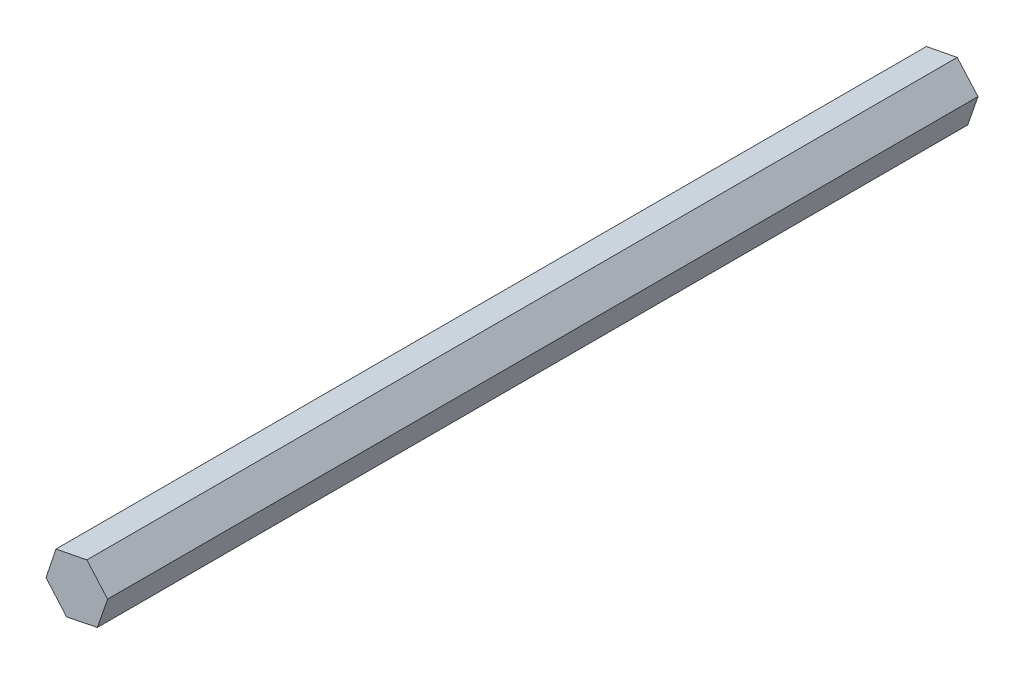
SolidWorks part; units mm, degrees
material "6061 Alloy"
ref_plane "Front Plane" through (0, 0, 0) normal (0, 0, 1) x (1, 0, 0)
ref_plane "Top Plane" through (0, 0, 0) normal (0, 1, 0) x (1, 0, 0)
ref_plane "Right Plane" through (0, 0, 0) normal (1, 0, 0) x (0, 0, -1)
ref_plane "Plane1" through (0, 0, -228.6) normal (0, 0, -1) x (-1, 0, 0)
sketch "Sketch1" plane through (0, 0, -228.6) normal (0, 0, -1) x (-1, 0, 0)
  line L0 (-2.3575, 6.9247) -> (-7.2099, 1.4275)
  line L1 (-7.2099, 1.4275) -> (-4.8182, -5.504)
  line L4 (-4.8182, -5.504) -> (2.3687, -6.9577)
  line L5 (2.3687, -6.9577) -> (7.1757, -1.4207)
  line L6 (7.1757, -1.4207) -> (4.8412, 5.5302)
  line L7 (4.8412, 5.5302) -> (-2.3575, 6.9247)
  circle A0 centre (0, 0) radius 6.35
  dimension "D1" = 12.7
extrude "Boss-Extrude1" add sketch "Sketch1" against normal blind 203.2
